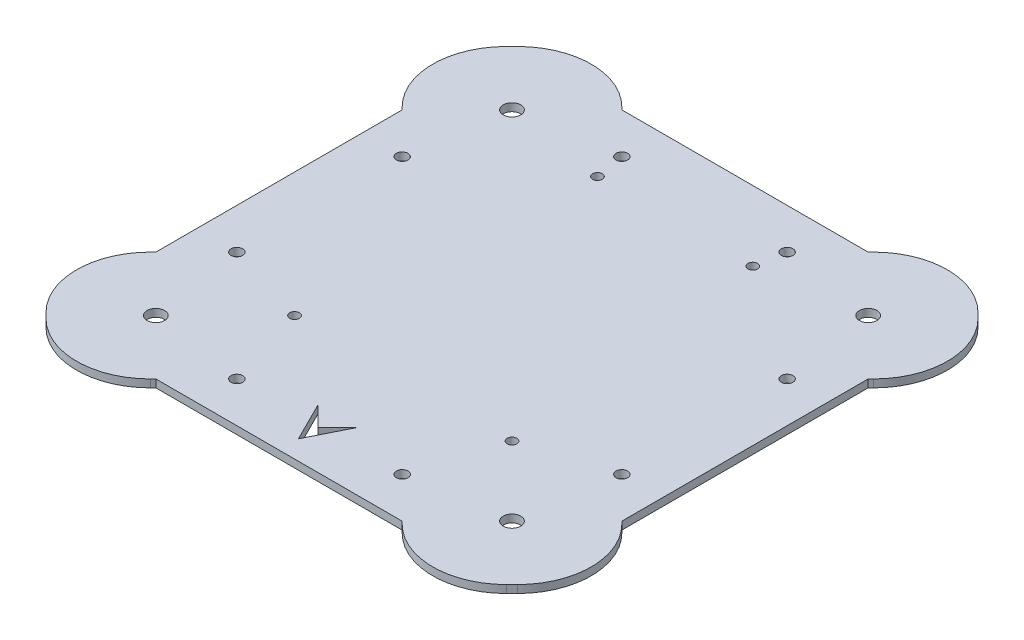
SolidWorks part; units mm, degrees
ref_plane "Front Plane" through (0, 0, 0) normal (0, 0, 1) x (1, 0, 0)
ref_plane "Top Plane" through (0, 0, 0) normal (0, 1, 0) x (1, 0, 0)
ref_plane "Right Plane" through (0, 0, 0) normal (1, 0, 0) x (0, 0, -1)
sketch "Sketch1" plane through (0, 0, 0) normal (0, 1, 0) x (1, 0, 0)
  line L1 (0, 0) -> (120, 0)
  line L2 (0, 0) -> (0, 120)
  line L3 (0, 120) -> (120, 120)
  line L4 (120, 0) -> (120, 120)
  dimension "D1" = 120
  dimension "D2" = 120
extrude "Boss-Extrude1" add sketch "Sketch1" along normal blind 2
sketch "Sketch2" plane through (0, 2, 0) normal (0, 1, 0) x (1, 0, 0)
  line L0 (60, 120) -> (60, 0) construction
  line L1 (120, 120) -> (0, 120) construction
  line L2 (0, 0) -> (120, 0) construction
  line L3 (120, 60) -> (0, 60) construction
  line L4 (120, 0) -> (120, 120) construction
  line L5 (0, 120) -> (0, 0) construction
  line L6 (60, 60) -> (120, 120) construction
  line L7 (105.8579, 105.8579) -> (120, 91.7157) construction
  line L8 (105.8579, 105.8579) -> (91.7157, 120) construction
  line L9 (91.7157, 120) -> (120, 91.7157)
  line L10 (91.7157, 120) -> (105.8579, 134.1421)
  line L11 (120, 91.7157) -> (134.1421, 105.8579)
  line L12 (105.8579, 134.1421) -> (134.1421, 105.8579)
  line L13 (0, 91.7157) -> (-14.1421, 105.8579)
  line L14 (14.1421, 134.1421) -> (-14.1421, 105.8579)
  line L15 (28.2843, 120) -> (14.1421, 134.1421)
  line L16 (28.2843, 120) -> (0, 91.7157)
  line L17 (28.2843, 0) -> (0, 28.2843)
  line L18 (28.2843, 0) -> (14.1421, -14.1421)
  line L19 (14.1421, -14.1421) -> (-14.1421, 14.1421)
  line L20 (0, 28.2843) -> (-14.1421, 14.1421)
  line L21 (120, 28.2843) -> (134.1421, 14.1421)
  line L22 (105.8579, -14.1421) -> (134.1421, 14.1421)
  line L23 (91.7157, 0) -> (105.8579, -14.1421)
  line L24 (91.7157, 0) -> (120, 28.2843)
  point P33 (120, 91.7157)
  point P34 (91.7157, 120)
  dimension "D1" = 40
  dimension "D2" = 20
extrude "Boss-Extrude3" add sketch "Sketch2" against normal blind 2
fillet "Fillet1" radius 19 8 edges at (134.1421, 1, -14.1421) (105.8579, 1, 14.1421) (14.1421, 1, 14.1421) (-14.1421, 1, -14.1421) (-14.1421, 1, -105.8579) (14.1421, 1, -134.1421) (105.8579, 1, -134.1421) (134.1421, 1, -105.8579)
sketch "Sketch4" plane through (0, 2, 0) normal (0, 1, 0) x (1, 0, 0)
  line L0 (60, 120) -> (60, 0) construction
  line L1 (91.7157, 120) -> (28.2843, 120) construction
  line L2 (28.2843, 0) -> (91.7157, 0) construction
  line L3 (0, 60) -> (120, 60) construction
  line L4 (0, 91.7157) -> (0, 28.2843) construction
  line L5 (120, 28.2843) -> (120, 91.7157) construction
  line L6 (28.2843, 0) -> (60, 31.7157) construction
  line L7 (35.0089, 35.0089) -> (6.7246, 6.7246) construction
  line L8 (27.5772, -0.7071) -> (28.2843, 0) construction
  circle A0 centre (38.7176, 10.4334) radius 1.5
  circle A1 centre (10.4334, 38.7176) radius 1.5
  circle A2 centre (81.2824, 10.4334) radius 1.5
  circle A3 centre (109.5666, 38.7176) radius 1.5
  circle A4 centre (38.7176, 109.5666) radius 1.5
  circle A5 centre (10.4334, 81.2824) radius 1.5
  circle A6 centre (81.2824, 109.5666) radius 1.5
  circle A7 centre (109.5666, 81.2824) radius 1.5
  dimension "D1" = 3
  dimension "D2" = 10.4334
extrude "Cut-Extrude2" cut sketch "Sketch4" against normal blind 2
sketch "Sketch5" plane through (0, 2, 0) normal (0, 1, 0) x (1, 0, 0)
  line L0 (0, 28.2843) -> (28.2843, 0) construction
  line L1 (60, 120) -> (60, 0) construction
  line L2 (91.7157, 120) -> (28.2843, 120) construction
  line L3 (28.2843, 0) -> (91.7157, 0) construction
  line L4 (0, 60) -> (120, 60) construction
  line L5 (0, 91.7157) -> (0, 28.2843) construction
  line L6 (120, 28.2843) -> (120, 91.7157) construction
  circle A0 centre (14.1421, 14.1421) radius 2.25
  circle A1 centre (105.8579, 14.1421) radius 2.25
  circle A2 centre (14.1421, 105.8579) radius 2.25
  circle A3 centre (105.8579, 105.8579) radius 2.25
  dimension "D1" = 4.5
extrude "Cut-Extrude3" cut sketch "Sketch5" against normal blind 10
sketch "Sketch6" plane through (0, 2, 0) normal (0, 1, 0) x (1, 0, 0)
  line L0 (60, 120) -> (60, 0) construction
  line L1 (91.7157, 120) -> (28.2843, 120) construction
  line L2 (28.2843, 0) -> (91.7157, 0) construction
  line L3 (0, 60) -> (120, 60) construction
  line L4 (0, 91.7157) -> (0, 28.2843) construction
  line L5 (120, 28.2843) -> (120, 91.7157) construction
  line L6 (60, 102) -> (80, 102) construction
  line L7 (60, 32) -> (88, 32) construction
  circle A0 centre (80, 102) radius 1.25
  circle A1 centre (88, 32) radius 1.25
  circle A2 centre (32, 32) radius 1.25
  circle A3 centre (40, 102) radius 1.25
  point P22 (60, 60)
  dimension "D1" = 2.5
  dimension "D2" = 40
  dimension "D4" = 56
  dimension "D3" = 70
  dimension "D5" = 39.598
extrude "Cut-Extrude4" cut sketch "Sketch6" against normal blind 15
sketch "Sketch7" plane through (0, 2, 0) normal (0, 1, 0) x (1, 0, 0)
  line L0 (60, 0) -> (60, 120) construction
  line L1 (28.2843, 0) -> (91.7157, 0) construction
  line L2 (91.7157, 120) -> (28.2843, 120) construction
  line L3 (60, 15) -> (65, 15) construction
  line L4 (65, 15) -> (60, 5)
  line L5 (60, 10) -> (65, 15)
  line L6 (55, 15) -> (60, 5)
  line L7 (60, 10) -> (55, 15)
  point P8 (60, 5)
  point P9 (60, 10)
  dimension "D1" = 5
  dimension "D2" = 10
  dimension "D3" = 5
  dimension "D4" = 5
extrude "Cut-Extrude5" cut sketch "Sketch7" against normal blind 2
